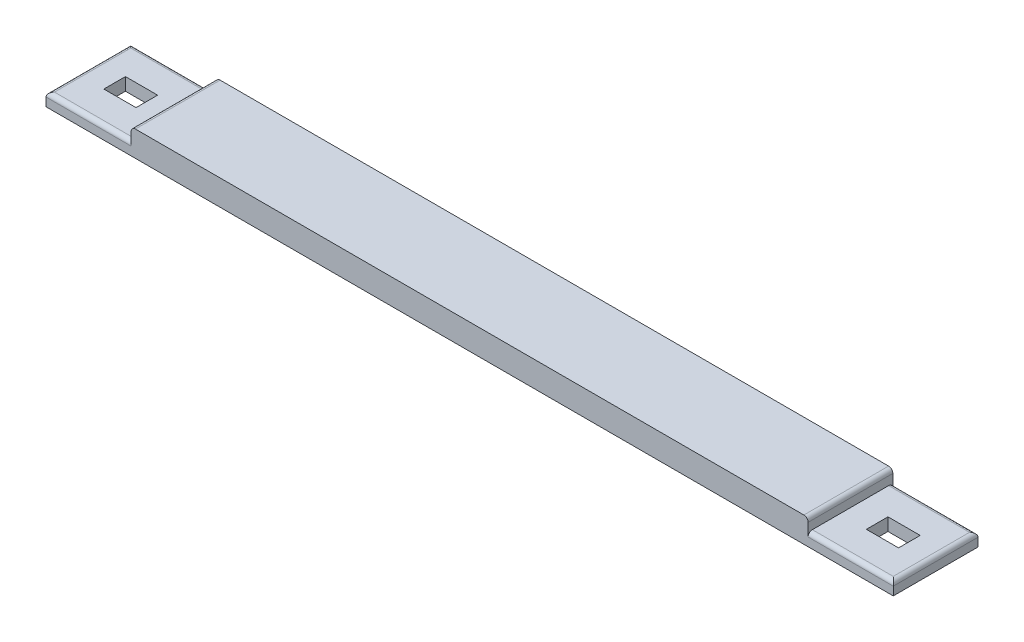
SolidWorks part; units mm, degrees
ref_plane "Front Plane" through (0, 0, 0) normal (0, 0, 1) x (1, 0, 0)
ref_plane "Top Plane" through (0, 0, 0) normal (0, 1, 0) x (1, 0, 0)
ref_plane "Right Plane" through (0, 0, 0) normal (1, 0, 0) x (0, 0, -1)
sketch "Sketch1" plane through (0, 0, 0) normal (0, 1, 0) x (1, 0, 0)
  line L0 (-90, 0) -> (0, 0) construction
  line L1 (-100, -10) -> (100, -10)
  line L2 (-100, -10) -> (-100, 10)
  line L3 (-100, 10) -> (100, 10)
  line L4 (100, -10) -> (100, 10)
  line L5 (-100, -10) -> (100, 10) construction
  line L6 (-100, 10) -> (100, -10) construction
  line L7 (-93.8, -2.55) -> (-86.2, -2.55)
  line L8 (-93.8, -2.55) -> (-93.8, 2.55)
  line L9 (-93.8, 2.55) -> (-86.2, 2.55)
  line L10 (-86.2, -2.55) -> (-86.2, 2.55)
  line L11 (-93.8, -2.55) -> (-86.2, 2.55) construction
  line L12 (-93.8, 2.55) -> (-86.2, -2.55) construction
  line L13 (0, -40.6881) -> (0, 40.6881) construction
  line L14 (93.8, 2.55) -> (86.2, 2.55)
  line L15 (86.2, -2.55) -> (86.2, 2.55)
  line L16 (93.8, -2.55) -> (86.2, -2.55)
  line L17 (93.8, -2.55) -> (93.8, 2.55)
  point P0 (0, 0)
  point P5 (-90, 0)
  dimension "D1" = 200
  dimension "D2" = 20
  dimension "D3" = 7.6
  dimension "D4" = 5.1
  dimension "D6" = 10
extrude "Boss-Extrude1" add sketch "Sketch1" along normal blind 6
sketch "Sketch2" plane through (0, 6, 0) normal (0, 1, 0) x (1, 0, 0)
  line L0 (-100, -10) -> (100, -10) construction
  line L1 (-100, 10) -> (-79.9, 10)
  line L2 (-100, 10) -> (-100, -10)
  line L3 (-100, -10) -> (-79.9, -10)
  line L4 (-79.9, 10) -> (-79.9, -10)
  line L6 (100, 10) -> (79.9, 10)
  line L7 (100, 10) -> (100, -10)
  line L8 (100, -10) -> (79.9, -10)
  line L9 (79.9, 10) -> (79.9, -10)
  point P11 (-75, -10)
  dimension "D1" = 20.1
extrude "Cut-Extrude1" cut sketch "Sketch2" against normal blind 3
fillet "Fillet1" radius 1 8 edges at (79.9, 6, 0) (-79.9, 6, 0) (-89.95, 3, 10) (-100, 3, 0) (-89.95, 3, -10) (89.95, 3, 10) (100, 3, 0) (89.95, 3, -10)
